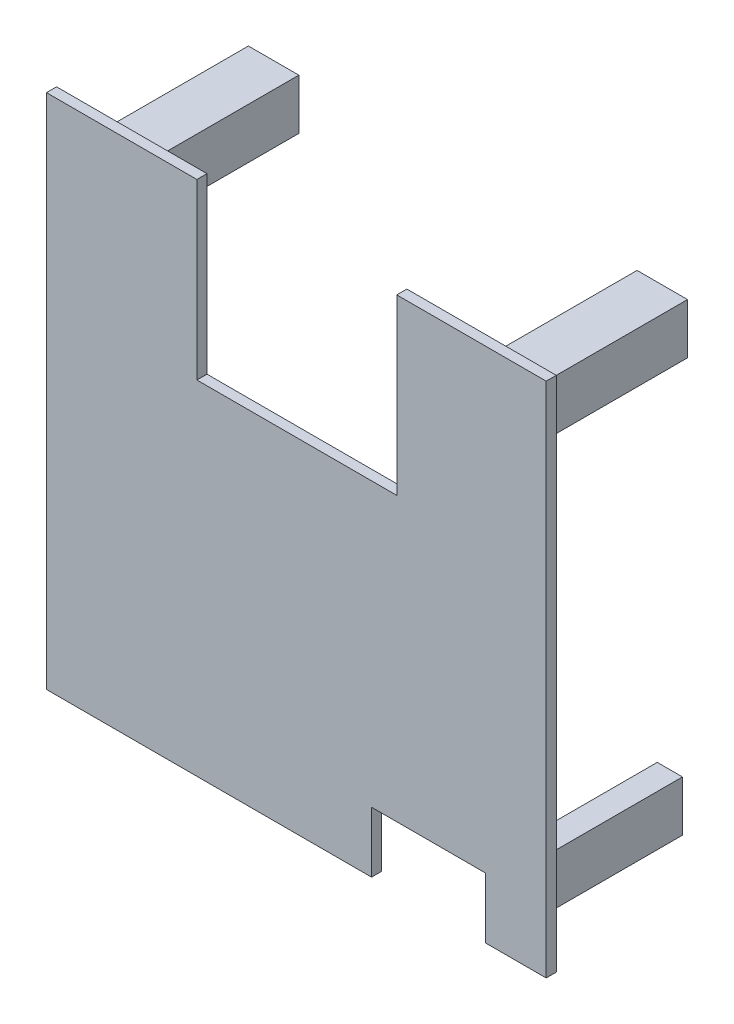
SolidWorks part; units mm, degrees
ref_plane "Plan de face" through (0, 0, 0) normal (0, 0, 1) x (1, 0, 0)
ref_plane "Plan de dessus" through (0, 0, 0) normal (0, 1, 0) x (1, 0, 0)
ref_plane "Plan de droite" through (0, 0, 0) normal (1, 0, 0) x (0, 0, -1)
sketch "Esquisse1" plane through (0, 0, 0) normal (0, 0, 1) x (1, 0, 0)
  line L1 (-26.1169, 16.5887) -> (23.3831, 16.5887)
  line L2 (-26.1169, 16.5887) -> (-26.1169, -34.6113)
  line L3 (-26.1169, -34.6113) -> (23.3831, -34.6113)
  line L4 (23.3831, 16.5887) -> (23.3831, -34.6113)
  dimension "D1" = 51.2
  dimension "D2" = 49.5
extrude "Boss.-Extru.1" add sketch "Esquisse1" along normal blind 1
sketch "Esquisse2" plane through (0, 0, 1) normal (0, 0, 1) x (1, 0, 0)
  line L5 (23.3831, -34.6113) -> (23.3831, 16.5887) construction
  line L7 (-26.1169, -34.6113) -> (23.3831, -34.6113) construction
  line L10 (17.3831, -34.6113) -> (6.0831, -34.6113)
  line L11 (17.3831, -34.6113) -> (17.3831, -28.6113)
  line L12 (17.3831, -28.6113) -> (6.0831, -28.6113)
  line L13 (6.0831, -34.6113) -> (6.0831, -28.6113)
  line L14 (23.3831, 16.5887) -> (-26.1169, 16.5887) construction
  line L15 (-11.2169, 16.5887) -> (8.5831, 16.5887)
  line L16 (-11.2169, 16.5887) -> (-11.2169, -0.6113)
  line L17 (-11.2169, -0.6113) -> (8.5831, -0.6113)
  line L18 (8.5831, 16.5887) -> (8.5831, -0.6113)
  dimension "D1" = 34
  dimension "D2" = 0
  dimension "D3" = 19.8
  dimension "D4" = 6
  dimension "D5" = 11.3
  dimension "D6" = 14.8
  dimension "D7" = 6
  dimension "D8" = 32.2
  dimension "D9" = 17.2
extrude "Enlèv. mat.-Extru.1" cut sketch "Esquisse2" against normal blind 5
sketch "Esquisse4" plane through (0, 0, 0) normal (0, 0, -1) x (-1, 0, 0)
  line L0 (11.2169, 16.5887) -> (26.1169, 16.5887) construction
  line L1 (18.1169, 13.5887) -> (23.1169, 13.5887)
  line L2 (18.1169, 13.5887) -> (18.1169, 8.5887)
  line L3 (18.1169, 8.5887) -> (23.1169, 8.5887)
  line L4 (23.1169, 13.5887) -> (23.1169, 8.5887)
  line L5 (26.1169, 16.5887) -> (26.1169, -34.6113) construction
  dimension "D1" = 5
  dimension "D2" = 5
  dimension "D3" = 3
  dimension "D4" = 3
extrude "Boss.-Extru.3" add sketch "Esquisse4" along normal blind 16
sketch "Esquisse5" plane through (0, 0, 0) normal (0, 0, -1) x (-1, 0, 0)
  line L0 (-23.3831, -34.6113) -> (-23.3831, 16.5887) construction
  line L1 (-19.8831, -27.6113) -> (-17.3831, -27.6113)
  line L2 (-19.8831, -27.6113) -> (-19.8831, -32.6113)
  line L3 (-19.8831, -32.6113) -> (-17.3831, -32.6113)
  line L4 (-17.3831, -27.6113) -> (-17.3831, -32.6113)
  line L5 (-17.3831, -34.6113) -> (-23.3831, -34.6113) construction
  dimension "D1" = 5
  dimension "D2" = 3.5
  dimension "D3" = 2
  dimension "D4" = 2.5
extrude "Boss.-Extru.4" add sketch "Esquisse5" along normal blind 16
sketch "Esquisse6" plane through (0, 0, 0) normal (0, 0, -1) x (-1, 0, 0)
  line L0 (-23.3831, 16.5887) -> (-8.5831, 16.5887) construction
  line L1 (-20.3831, 13.5887) -> (-15.3831, 13.5887)
  line L2 (-20.3831, 13.5887) -> (-20.3831, 8.5887)
  line L3 (-20.3831, 8.5887) -> (-15.3831, 8.5887)
  line L4 (-15.3831, 13.5887) -> (-15.3831, 8.5887)
  line L5 (-23.3831, -34.6113) -> (-23.3831, 16.5887) construction
  dimension "D1" = 3
  dimension "D2" = 3
  dimension "D3" = 5
  dimension "D4" = 5
extrude "Boss.-Extru.5" add sketch "Esquisse6" along normal blind 16
sketch "Esquisse7" plane through (0, 0, 0) normal (0, 0, -1) x (-1, 0, 0)
  line L0 (26.1169, 16.5887) -> (26.1169, -34.6113) construction
  line L1 (19.1169, -27.6113) -> (23.1169, -27.6113)
  line L2 (19.1169, -27.6113) -> (19.1169, -31.6113)
  line L3 (19.1169, -31.6113) -> (23.1169, -31.6113)
  line L4 (23.1169, -27.6113) -> (23.1169, -31.6113)
  line L5 (26.1169, -34.6113) -> (-6.0831, -34.6113) construction
  dimension "D1" = 3
  dimension "D2" = 3
  dimension "D3" = 4
  dimension "D4" = 4
extrude "Boss.-Extru.6" add sketch "Esquisse7" along normal blind 16
